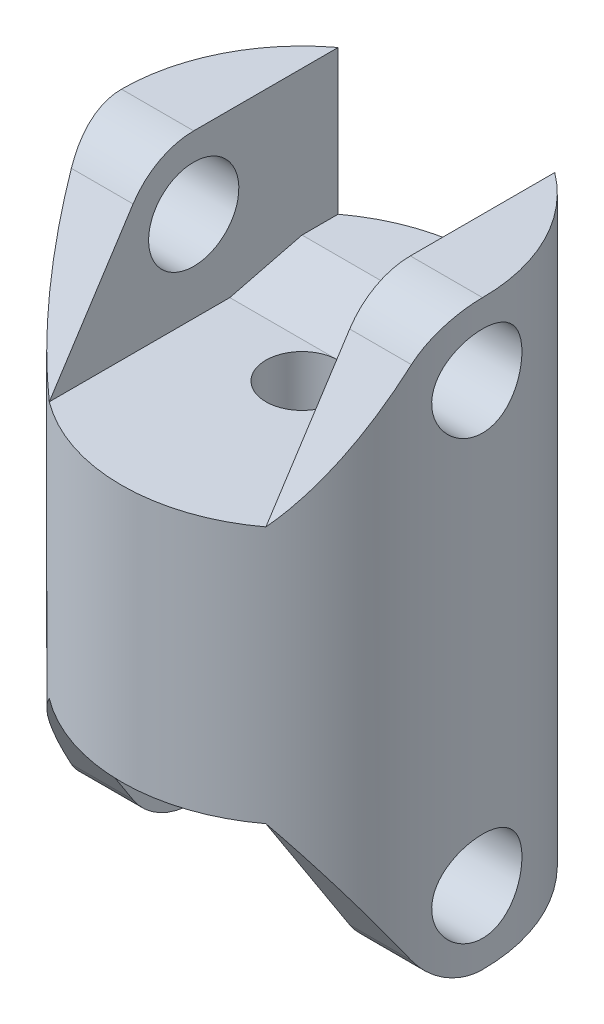
SolidWorks part; units mm, degrees
ref_plane "Front Plane" through (0, 0, 0) normal (0, 0, 1) x (1, 0, 0)
ref_plane "Top Plane" through (0, 0, 0) normal (0, 1, 0) x (1, 0, 0)
ref_plane "Right Plane" through (0, 0, 0) normal (1, 0, 0) x (0, 0, -1)
sketch "Sketch1" plane through (0, 0, 0) normal (0, 1, 0) x (1, 0, 0)
  circle A0 centre (0, 0) radius 12.7
  dimension "D1" = 25.4
extrude "Boss-Extrude1" add sketch "Sketch1" along normal blind 40.9448
sketch "Sketch2" plane through (0, 40.9448, 0) normal (0, 1, 0) x (1, 0, 0)
  line L0 (7.62, 10.16) -> (7.62, -10.16)
  line L1 (-7.62, 10.16) -> (-7.62, -10.16)
  arc A0 (-7.62, -10.16) -> (7.62, -10.16) centre (0, 0) ccw
  arc A1 (7.62, 10.16) -> (-7.62, 10.16) centre (0, 0) ccw
  dimension "D2" = 25.4
  dimension "D1" = 7.62
  dimension "D3" = 7.62
extrude "Cut-Extrude1" cut sketch "Sketch2" against normal blind 11.43
sketch "Sketch3" plane through (0, 0, 0) normal (0, -1, 0) x (1, 0, 0)
  line L1 (-7.62, 10.16) -> (-7.62, -10.16)
  line L3 (7.62, 10.16) -> (7.62, -10.16)
  arc A4 (-7.62, 10.16) -> (7.62, 10.16) centre (0, 0) cw
  arc A5 (-7.62, -10.16) -> (7.62, -10.16) centre (0, 0) ccw
  dimension "D1" = 15.24
extrude "Cut-Extrude2" cut sketch "Sketch3" against normal blind 11.43
sketch "Sketch4" plane through (-7.62, 0, 0) normal (1, 0, 0) x (0, 0, -1)
  line L0 (10.16, 40.9448) -> (-10.16, 40.9448) construction
  line L5 (-10.16, 0) -> (10.16, 0) construction
  line L6 (10.16, 40.9448) -> (-10.16, 40.9448) construction
  line L7 (0, 40.9448) -> (-10.16, 40.9448)
  line L8 (-10.16, 40.9448) -> (-10.16, 29.5148)
  line L9 (-10.16, 29.5148) -> (-4.2649, 38.6247)
  line L15 (-10.16, 0) -> (10.16, 0) construction
  line L16 (-4.2649, 2.3201) -> (-10.16, 11.43)
  line L17 (-10.16, 11.43) -> (-10.16, 0)
  line L18 (-10.16, 0) -> (0, 0)
  circle A0 centre (0, 35.8648) radius 3.175
  circle A2 centre (0, 5.08) radius 3.175
  arc A4 (0, 40.9448) -> (-4.2649, 38.6247) centre (0, 35.8648) ccw
  arc A6 (0, 0) -> (-4.2649, 2.3201) centre (0, 5.08) cw
  dimension "D1" = 6.35
  dimension "D3" = 6.35
  dimension "D2" = 5.08
  dimension "D4" = 5.08
  dimension "D5" = 0
extrude "Cut-Extrude3" cut sketch "Sketch4" against normal through all both and the other way through all
sketch "Sketch5" plane through (0, 29.5148, 0) normal (0, 1, 0) x (1, 0, 0)
  circle A0 centre (0, 0) radius 2.54
  dimension "D1" = 5.08
extrude "Cut-Extrude4" cut sketch "Sketch5" against normal through all
sketch "Sketch6" plane through (-7.62, 0, 0) normal (1, 0, 0) x (0, 0, -1)
  line L0 (2.54, 29.5148) -> (10.16, 29.5148)
  line L1 (10.16, 29.5148) -> (-10.16, 29.5148) construction
  line L2 (10.16, 29.5148) -> (10.16, 30.7848)
  line L3 (10.16, 29.5148) -> (10.16, 40.9448) construction
  line L4 (10.16, 30.7848) -> (7.62, 30.7848)
  line L5 (7.62, 30.7848) -> (2.54, 29.5148)
  point P5 (0, 29.5148)
  dimension "D1" = 2.54
  dimension "D2" = 1.27
  dimension "D3" = 2.54
extrude "Boss-Extrude2" add sketch "Sketch6" along normal up to surface (15.24 mm away) up to face at (7.62, 35.8648, -3.175)
sketch "Sketch7" plane through (0, 29.5148, 0) normal (0, 1, 0) x (1, 0, 0)
  line L0 (-7.62, 10.16) -> (7.62, 10.16)
  arc A0 (7.62, 10.16) -> (-7.62, 10.16) centre (0, 0) ccw
  arc M1 (7.62, 10.16) -> (-7.62, 10.16) centre (0, 0) ccw
  line M2 (-7.62, 10.16) -> (7.62, 10.16)
extrude "Boss-Extrude3" add sketch "Sketch7" along normal up to surface (1.27 mm away) contours M2 M1 up to face at (0, 30.7848, -8.89)
